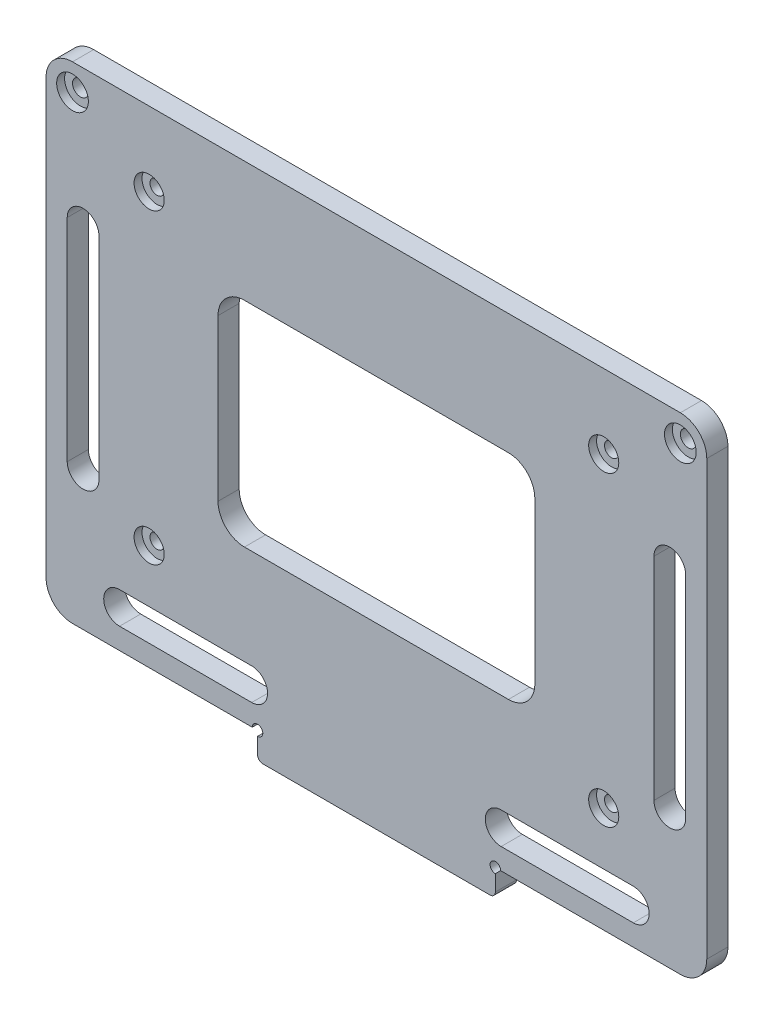
SolidWorks part; units mm, degrees
ref_plane "前视基准面" through (0, 0, 0) normal (0, 0, 1) x (1, 0, 0)
ref_plane "上视基准面" through (0, 0, 0) normal (0, 1, 0) x (1, 0, 0)
ref_plane "右视基准面" through (0, 0, 0) normal (1, 0, 0) x (0, 0, -1)
other "Configuration Table"
sketch "草图1" plane through (0, 0, 0) normal (0, 0, 1) x (1, 0, 0)
  line L1 (-22.5, 2.5) -> (22.5, 2.5)
  line L2 (-22.5, 2.5) -> (-22.5, -2.5)
  line L3 (-22.5, -2.5) -> (22.5, -2.5)
  line L4 (22.5, 2.5) -> (22.5, -2.5)
  line L5 (-22.5, 2.5) -> (22.5, -2.5) construction
  line L6 (-22.5, -2.5) -> (22.5, 2.5) construction
  point P0 (0, 0)
  dimension "D1" = 45
  dimension "D2" = 5
extrude "凸台-拉伸1" add sketch "草图1" along normal blind 4
sketch "草图2" plane through (0, 0, 0) normal (0, 0, -1) x (-1, 0, 0)
  line L0 (-62.5, 2.5) -> (62.5, 2.5)
  line L1 (-62.5, 2.5) -> (-62.5, 94.525)
  line L2 (62.5, 2.5) -> (62.5, 94.525)
  line L3 (-62.5, 94.525) -> (62.5, 94.525)
  line L4 (-22.5, 2.5) -> (-22.5, -2.5)
  line L5 (-22.5, -2.5) -> (22.5, -2.5)
  line L6 (22.5, -2.5) -> (22.5, 2.5)
  line L7 (22.5, 2.5) -> (-22.5, 2.5)
  line L8 (-22.5, 2.5) -> (-22.5, -2.5)
  line L9 (-22.5, -2.5) -> (22.5, -2.5)
  line L10 (22.5, -2.5) -> (22.5, 2.5)
  line L11 (22.5, 2.5) -> (-22.5, 2.5)
  line L12 (72.5, 94.525) -> (-72.5, 94.525) construction
  line L13 (72.5, 94.525) -> (-72.5, 94.525) construction
  line L14 (-62.5, 48.5125) -> (62.5, 48.5125) construction
  line L15 (-55.5, 68.5125) -> (-55.5, 28.5125) construction
  line L16 (-43, 80.5) -> (43, 80.5) construction
  line L17 (-43, 80.5) -> (-43, 22.5) construction
  line L22 (-43, 22.5) -> (43, 22.5) construction
  line L23 (43, 80.5) -> (43, 22.5) construction
  line L26 (-43, 80.5) -> (43, 22.5) construction
  line L29 (-43, 22.5) -> (43, 80.5) construction
  line L30 (-52.5, 68.5125) -> (-52.5, 28.5125)
  line L31 (-58.5, 68.5125) -> (-58.5, 28.5125)
  line L32 (55.5, 68.5125) -> (55.5, 28.5125) construction
  line L33 (58.5, 68.5125) -> (58.5, 28.5125)
  line L34 (52.5, 68.5125) -> (52.5, 28.5125)
  line L35 (0, 94.525) -> (0, 2.5) construction
  line L36 (-29.9694, 71.7119) -> (29.9694, 71.7119)
  line L37 (-29.9694, 71.7119) -> (-29.9694, 31.2881)
  line L38 (-29.9694, 31.2881) -> (29.9694, 31.2881)
  line L39 (29.9694, 71.7119) -> (29.9694, 31.2881)
  line L40 (-29.9694, 71.7119) -> (29.9694, 31.2881) construction
  line L41 (-29.9694, 31.2881) -> (29.9694, 71.7119) construction
  line L42 (-48.5972, 9.5) -> (-23.5972, 9.5) construction
  line L43 (-48.5972, 12.5) -> (-23.5972, 12.5)
  line L44 (-48.5972, 6.5) -> (-23.5972, 6.5)
  line L45 (48.5972, 9.5) -> (23.5972, 9.5) construction
  line L46 (48.5972, 12.5) -> (23.5972, 12.5)
  line L47 (48.5972, 6.5) -> (23.5972, 6.5)
  circle A0 centre (-57.5, 89.525) radius 1.5 construction
  circle A1 centre (57.5, 89.525) radius 1.5 construction
  circle A2 centre (-57.5, 89.525) radius 1.5
  circle A3 centre (57.5, 89.525) radius 1.5
  circle A18 centre (-43, 80.5) radius 1.35
  circle A19 centre (43, 80.5) radius 1.35
  circle A20 centre (43, 22.5) radius 1.35
  circle A21 centre (-43, 22.5) radius 1.35
  arc A22 (-52.5, 68.5125) -> (-58.5, 68.5125) centre (-55.5, 68.5125) ccw
  arc A23 (-58.5, 28.5125) -> (-52.5, 28.5125) centre (-55.5, 28.5125) ccw
  arc A24 (58.5, 68.5125) -> (52.5, 68.5125) centre (55.5, 68.5125) ccw
  arc A25 (52.5, 28.5125) -> (58.5, 28.5125) centre (55.5, 28.5125) ccw
  arc A26 (-48.5972, 12.5) -> (-48.5972, 6.5) centre (-48.5972, 9.5) ccw
  arc A27 (-23.5972, 6.5) -> (-23.5972, 12.5) centre (-23.5972, 9.5) ccw
  arc A28 (48.5972, 12.5) -> (48.5972, 6.5) centre (48.5972, 9.5) cw
  arc A29 (23.5972, 6.5) -> (23.5972, 12.5) centre (23.5972, 9.5) cw
  point P23 (0, 51.5)
  point P31 (-55.5, 48.5125)
  point P38 (55.5, 48.5125)
  point P43 (0, 51.5)
  point P52 (-36.0972, 9.5)
  point P57 (-36.0972, 9.5)
  point P60 (36.0972, 9.5)
  line M8 (22.5, 2.5) -> (-22.5, 2.5)
  dimension "D4" = 2.7
  dimension "D8" = 40
  dimension "D11" = 40
  dimension "D7" = 3
  dimension "D10" = 3
  dimension "D13" = 3
  dimension "D2" = 86
  dimension "D3" = 58
  dimension "D5" = 20
  dimension "D6" = 4
  dimension "D9" = 4
  dimension "D12" = 4
  dimension "D14" = 25
  dimension "D1" = 0
extrude "凸台-拉伸2" add sketch "草图2" against normal blind 4 contours L3 L1 L0 L2 A3 A2 M8
sketch "草图3" plane through (0, 0, 0) normal (0, 0, -1) x (-1, 0, 0)
  line L8 (-22.5, 2.5) -> (-22.5, -2.5)
  line L9 (-22.5, -2.5) -> (22.5, -2.5)
  line L10 (22.5, -2.5) -> (22.5, 2.5)
  line L11 (22.5, 2.5) -> (62.5, 2.5)
  line L12 (62.5, 2.5) -> (62.5, 94.525)
  line L13 (62.5, 94.525) -> (-62.5, 94.525)
  line L14 (-62.5, 94.525) -> (-62.5, 2.5)
  line L15 (-62.5, 2.5) -> (-22.5, 2.5)
  line L16 (-22.5, 2.5) -> (-22.5, -2.5)
  line L17 (-22.5, -2.5) -> (22.5, -2.5)
  line L18 (22.5, -2.5) -> (22.5, 2.5)
  line L19 (22.5, 2.5) -> (62.5, 2.5)
  line L20 (62.5, 2.5) -> (62.5, 94.525)
  line L21 (62.5, 94.525) -> (-62.5, 94.525)
  line L22 (-62.5, 94.525) -> (-62.5, 2.5)
  line L23 (-62.5, 2.5) -> (-22.5, 2.5)
  circle A0 centre (-22.5, 2.5) radius 1
  circle A1 centre (22.5, 2.5) radius 1
  line M11 (-22.5, 2.5) -> (-22.5, -2.5)
  line M14 (22.5, 2.5) -> (62.5, 2.5)
  dimension "D2" = 2
  dimension "D1" = 0
extrude "切除-拉伸1" cut sketch "草图3" against normal blind 4 contours A0 L23 M11 | A1 L18 M14
fillet "圆角1" radius 5 8 edges at (62.5, 2.5, 2) (-62.5, 2.5, 2) (-62.5, 94.525, 2) (62.5, 94.525, 2) (-29.9694, 71.7119, 2) (-29.9694, 31.2881, 2) (29.9694, 31.2881, 2) (29.9694, 71.7119, 2)
fillet "圆角2" radius 1 2 edges at (22.5, -2.5, 2) (-22.5, -2.5, 2)
sketch "草图4" plane through (0, 0, 4) normal (0, 0, 1) x (1, 0, 0)
  circle A12 centre (43, 22.5) radius 1.35 construction
  circle A13 centre (43, 80.5) radius 1.35 construction
  circle A14 centre (-43, 22.5) radius 1.35 construction
  circle A15 centre (-43, 80.5) radius 1.35 construction
  circle A16 centre (43, 22.5) radius 1.35
  circle A17 centre (43, 80.5) radius 1.35
  circle A18 centre (-43, 22.5) radius 1.35
  circle A19 centre (-43, 80.5) radius 1.35
  circle A20 centre (57.5, 89.525) radius 1.5 construction
  circle A21 centre (-57.5, 89.525) radius 1.5 construction
  circle A22 centre (57.5, 89.525) radius 1.5
  circle A23 centre (-57.5, 89.525) radius 1.5
  circle A24 centre (43, 22.5) radius 2.85
  circle A25 centre (43, 80.5) radius 2.85
  circle A26 centre (-43, 22.5) radius 2.85
  circle A27 centre (-43, 80.5) radius 2.85
  circle A28 centre (57.5, 89.525) radius 3
  circle A29 centre (-57.5, 89.525) radius 3
  dimension "D1" = 1.5
extrude "切除-拉伸2" cut sketch "草图4" against normal blind 1.5
